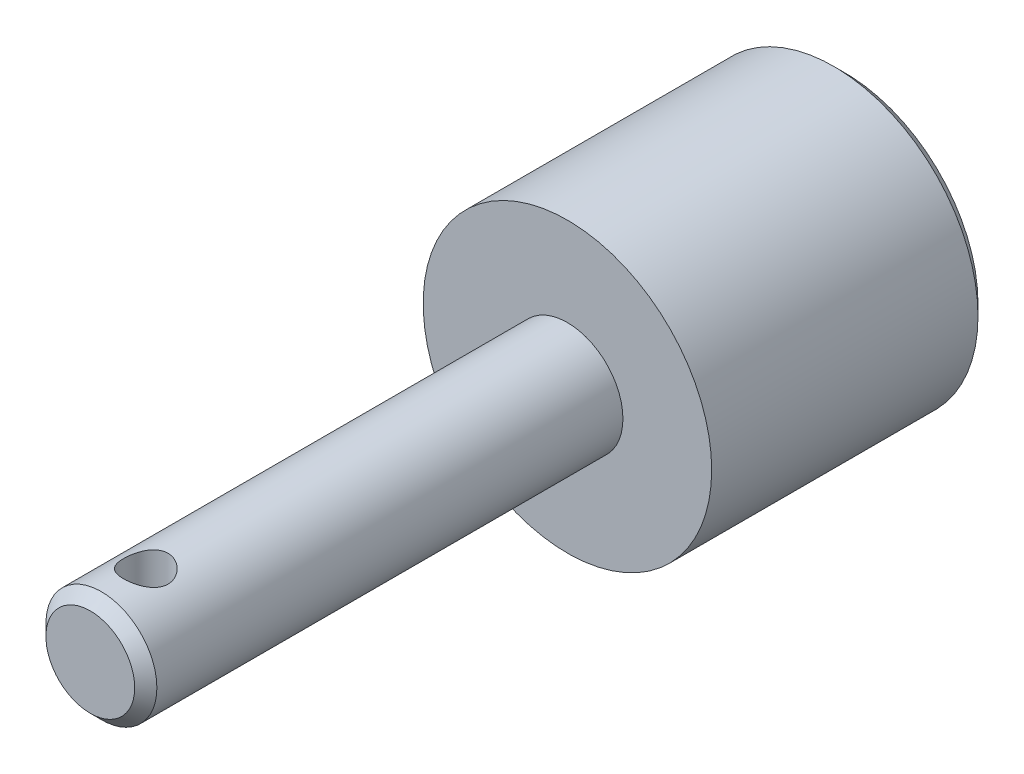
SolidWorks part; units mm, degrees
material "C40 or 38NiCrMo4"
ref_plane "Piano frontale" through (0, 0, 0) normal (0, 0, 1) x (1, 0, 0)
ref_plane "Piano superiore" through (0, 0, 0) normal (0, 1, 0) x (1, 0, 0)
ref_plane "Piano destro" through (0, 0, 0) normal (1, 0, 0) x (0, 0, -1)
sketch "Schizzo1" plane through (0, 0, 0) normal (0, 0, 1) x (1, 0, 0)
  circle A0 centre (0, 0) radius 26
  dimension "D1" = 52
extrude "Estrusione1" add sketch "Schizzo1" along normal blind 50
sketch "Schizzo2" plane through (0, 0, 50) normal (0, 0, 1) x (1, 0, 0)
  circle A0 centre (0, 0) radius 10
  dimension "D1" = 20
extrude "Estrusione2" add sketch "Schizzo2" along normal blind 86
chamfer "Smusso1" distance 2 angle 45 1 edges at (10, 0, 136)
sketch "Schizzo3" plane through (0, 0, 0) normal (0, 1, 0) x (1, 0, 0)
  line L0 (-10, -50) -> (10, -50) construction
  circle A0 centre (0, -126) radius 4
  dimension "D1" = 8
  dimension "D2" = 76
extrude "Estrusione3" cut sketch "Schizzo3" against normal through all and the other way through all
chamfer "Smusso2" distance 2 angle 45 1 edges at (26, 0, 0)
